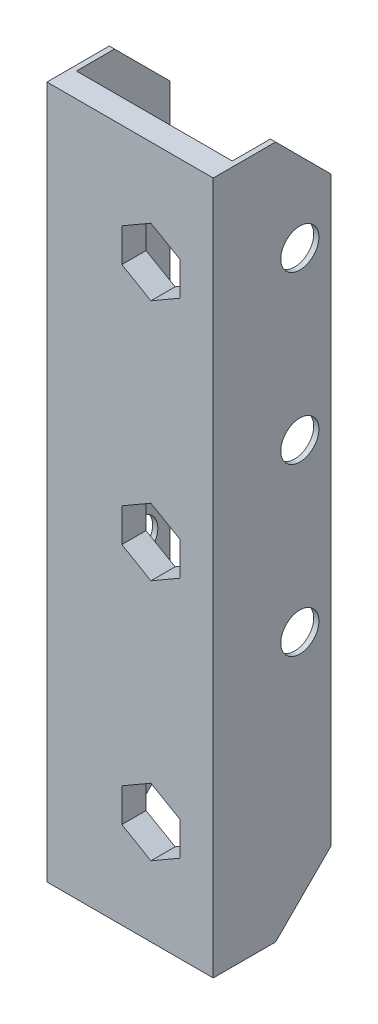
SolidWorks part; units mm, degrees
ref_plane "Front" through (0, 0, 0) normal (0, 0, 1) x (1, 0, 0)
ref_plane "Top" through (0, 0, 0) normal (0, 1, 0) x (1, 0, 0)
ref_plane "Right" through (0, 0, 0) normal (1, 0, 0) x (0, 0, -1)
sketch "Sketch1" plane through (0, 0, 0) normal (0, 1, 0) x (1, 0, 0)
  line L0 (0, 0) -> (0, 17)
  line L1 (0, 17) -> (0.75, 17)
  line L2 (0.75, 17) -> (0.75, 3.5)
  line L3 (0.75, 3.5) -> (23.25, 3.5)
  line L4 (23.25, 3.5) -> (23.25, 17)
  line L5 (23.25, 17) -> (24, 17)
  line L6 (24, 17) -> (24, 0)
  line L7 (24, 0) -> (0, 0)
  dimension "D1" = 3.5
  dimension "D2" = 0.75
  dimension "D3" = 24
  dimension "D4" = 17
extrude "Boss-Extrude1" add sketch "Sketch1" along normal blind 100 contours L3 L4 L5 L6 L7 L0 L1 L2
sketch "Sketch2" plane through (0, 0, 0) normal (0, 0, 1) x (1, 0, 0)
  line L0 (24, 100) -> (0, 100) construction
  line L1 (15, 80.1503) -> (19.2, 82.5751)
  line L2 (19.2, 82.5751) -> (19.2, 87.4249)
  line L3 (19.2, 87.4249) -> (15, 89.8497)
  line L4 (15, 89.8497) -> (10.8, 87.4249)
  line L5 (10.8, 87.4249) -> (10.8, 82.5751)
  line L6 (10.8, 82.5751) -> (15, 80.1503)
  line L7 (15, 45.1503) -> (19.2, 47.5751)
  line L8 (19.2, 47.5751) -> (19.2, 52.4249)
  line L9 (19.2, 52.4249) -> (15, 54.8497)
  line L10 (15, 54.8497) -> (10.8, 52.4249)
  line L11 (10.8, 52.4249) -> (10.8, 47.5751)
  line L12 (10.8, 47.5751) -> (15, 45.1503)
  line L13 (15, 19.8497) -> (10.8, 17.4249)
  line L14 (10.8, 17.4249) -> (10.8, 12.5751)
  line L15 (10.8, 12.5751) -> (15, 10.1503)
  line L16 (15, 10.1503) -> (19.2, 12.5751)
  line L17 (19.2, 12.5751) -> (19.2, 17.4249)
  line L18 (19.2, 17.4249) -> (15, 19.8497)
  line L19 (24, 100) -> (24, 0) construction
  circle A0 centre (15, 85) radius 4.2 construction
  circle A1 centre (15, 50) radius 4.2 construction
  circle A2 centre (15, 15) radius 4.2 construction
  dimension "D1" = 35
  dimension "D2" = 35
  dimension "D3" = 15
  dimension "D4" = 8.4
  dimension "D5" = 9
extrude "Cut-Extrude1" cut sketch "Sketch2" against normal through all both and the other way through all contours L11 L12 L7 L8 L9 L10 | L17 L18 L13 L14 L15 L16 | L5 L6 L1 L2 L3 L4
hole_wizard "M5 Clearance Hole1" positions "Sketch3" profile "Sketch4" hole size "M5" standard "ISO" end condition through all
sketch "Sketch3" plane through (24, 0, 0) normal (1, 0, 0) x (0, 0, -1)
  line L0 (17, 100) -> (0, 100) construction
  line L2 (3.5, 100) -> (3.5, 0) construction
  point P0 (12.5, 85)
  point P2 (12.5, 37)
  point P4 (12.5, 61)
  dimension "D1" = 24
  dimension "D2" = 24
  dimension "D3" = 15
  dimension "D4" = 9
sketch "Sketch4" plane through (24, 85, -12.5) normal (0, 1, 0) x (0, 0, -1)
  line L0 (0, 0) -> (0, 24)
  line L1 (0, 24) -> (2.75, 24)
  line L2 (2.75, 24) -> (2.75, 0)
  line L5 (2.75, 0) -> (0, 0)
  line L11 (0, -6.35) -> (0, 107.95) construction
  dimension "Thru Hole Dia." = 5.5
  dimension "Thru Hole Depth" = 24
chamfer "Chamfer1" distance 8 angle 45 4 edges at (0.375, 100, -17) (23.625, 100, -17) (23.625, 0, -17) (0.375, 0, -17)
